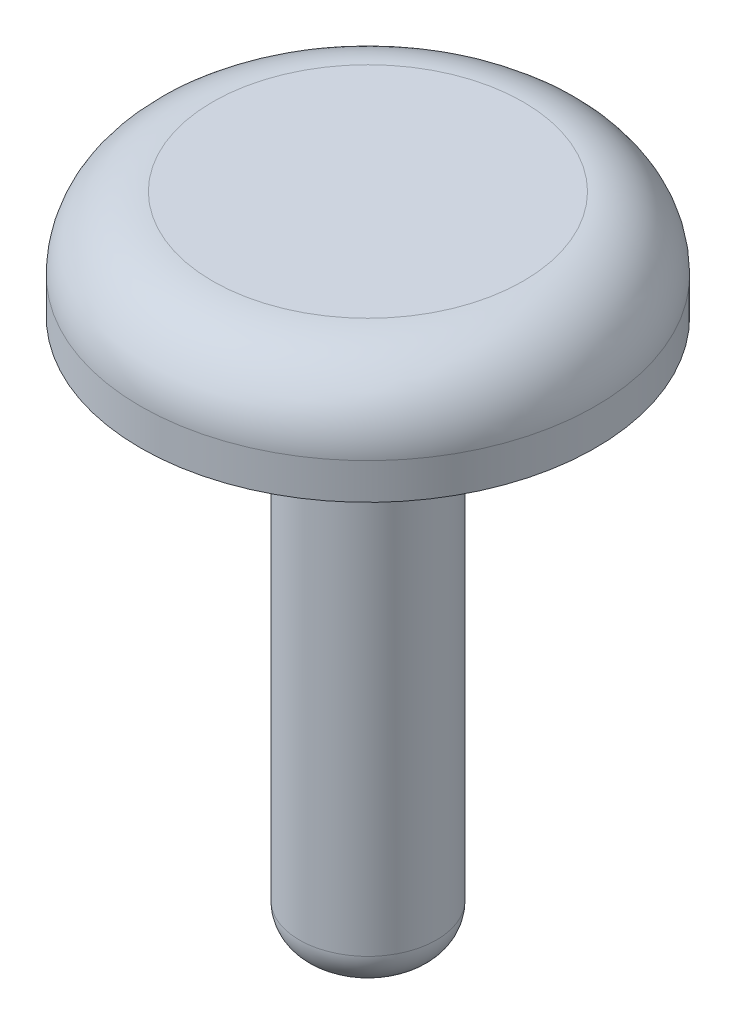
SolidWorks part; units mm, degrees
ref_plane "Alzado" through (0, 0, 0) normal (0, 0, 1) x (1, 0, 0)
ref_plane "Planta" through (0, 0, 0) normal (0, 1, 0) x (1, 0, 0)
ref_plane "Vista lateral" through (0, 0, 0) normal (1, 0, 0) x (0, 0, -1)
sketch "Croquis1" plane through (0, 0, 0) normal (0, 1, 0) x (1, 0, 0)
  circle A0 centre (0, 0) radius 0.95
extrude "Saliente-Extruir1" add sketch "Croquis1" along normal blind 9
sketch "Croquis2" plane through (0, 9, 0) normal (0, 1, 0) x (1, 0, 0)
  circle A0 centre (0, 0) radius 3.15
extrude "Saliente-Extruir2" add sketch "Croquis2" along normal blind 0.0001 and the other way blind 1.5
fillet "Redondeo3" radius 0.5 1 edges at (0, 0, 0.95)
fillet "Redondeo5" radius 1 1 edges at (0, 9.0001, 3.15)
sketch "Croquis4" plane through (0, 7.5, 0) normal (0, -1, 0) x (-1, 0, 0)
  circle A1 centre (0, 0) radius 2.65
  circle M2 centre (0, 0) radius 0.95
extrude "Cortar-Extruir4" cut sketch "Croquis4" against normal blind 1 contours A1 M2
